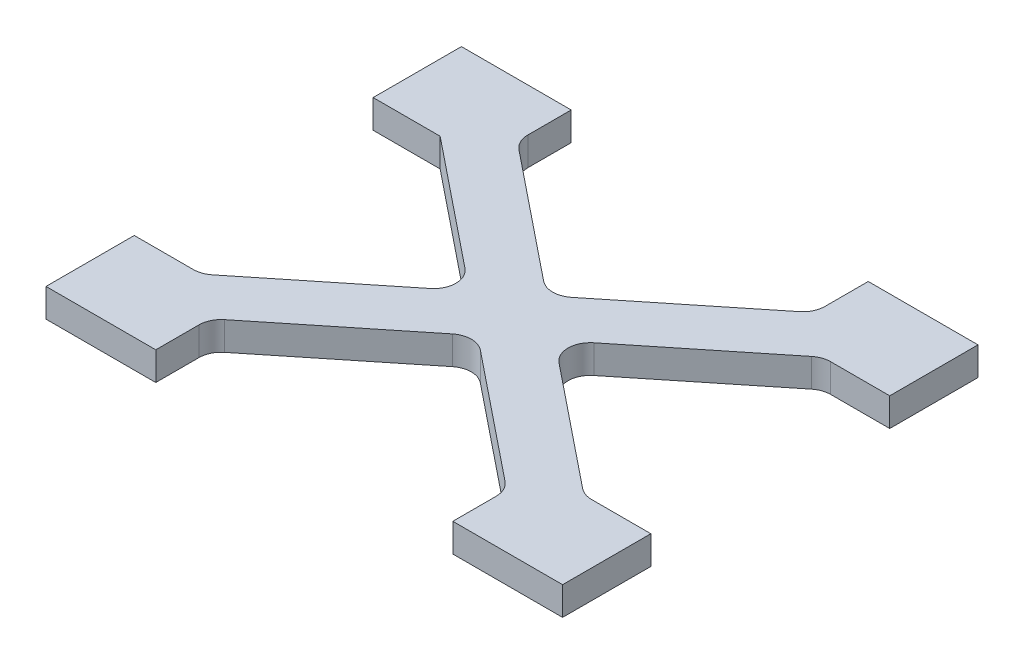
SolidWorks part; units mm, degrees
ref_plane "Front Plane" through (0, 0, 0) normal (0, 0, 1) x (1, 0, 0)
ref_plane "Top Plane" through (0, 0, 0) normal (0, 1, 0) x (1, 0, 0)
ref_plane "Right Plane" through (0, 0, 0) normal (1, 0, 0) x (0, 0, -1)
sketch "Sketch1" plane through (0, 0, 0) normal (0, 1, 0) x (1, 0, 0)
  line L1 (57.825, 46.5) -> (-57.825, 46.5) construction
  line L2 (57.825, 46.5) -> (57.825, -46.5) construction
  line L3 (57.825, -46.5) -> (-57.825, -46.5) construction
  line L4 (-57.825, 46.5) -> (-57.825, -46.5) construction
  line L5 (-57.825, 46.5) -> (57.825, -46.5) construction
  line L6 (-57.825, 26.7384) -> (-42.825, 26.7384)
  line L36 (-42.825, 26.7384) -> (-9.5745, 0)
  line L37 (-9.5745, 0) -> (-42.825, -26.7384)
  line L38 (-42.825, -26.7384) -> (-57.825, -26.7384)
  line L39 (-57.825, -26.7384) -> (-57.825, -46.5)
  line L40 (-57.825, -46.5) -> (-33.2505, -46.5)
  line L41 (-33.2505, -46.5) -> (-33.2505, -34.4377)
  line L42 (-33.2505, -34.4377) -> (0, -7.6993)
  line L43 (0, -7.6993) -> (33.2505, -34.4377)
  line L44 (33.2505, -34.4377) -> (33.2505, -46.5)
  line L45 (33.2505, -46.5) -> (57.825, -46.5)
  line L46 (57.825, -46.5) -> (57.825, -26.7384)
  line L47 (57.825, -26.7384) -> (42.825, -26.7384)
  line L48 (42.825, -26.7384) -> (9.5745, 0)
  line L49 (9.5745, 0) -> (42.825, 26.7384)
  line L50 (42.825, 26.7384) -> (57.825, 26.7384)
  line L51 (57.825, 26.7384) -> (57.825, 46.5)
  line L52 (57.825, 46.5) -> (33.2505, 46.5)
  line L53 (33.2505, 46.5) -> (33.2505, 34.4377)
  line L54 (33.2505, 34.4377) -> (0, 7.6993)
  line L55 (0, 7.6993) -> (-33.2505, 34.4377)
  line L56 (-33.2505, 34.4377) -> (-33.2505, 46.5)
  line L57 (-33.2505, 46.5) -> (-57.825, 46.5)
  line L58 (-57.825, 46.5) -> (-57.825, 26.7384)
  line L59 (-57.825, -46.5) -> (57.825, 46.5) construction
  line L65 (42.825, 26.7384) -> (33.2505, 34.4377) construction
  point P7 (0, 0)
  point P23 (50.7888, 42.9396)
  point P27 (50.3534, 42.5715)
  point P31 (0, 7.857)
  point P32 (-16.0474, 21.4243)
  dimension "D1" = 115.65
  dimension "D2" = 93
  dimension "D3" = 12
  dimension "D4" = 15
extrude "Boss-Extrude1" add sketch "Sketch1" along normal blind 6.35
fillet "Fillet1" radius 5 11 edges at (-33.2505, 3.175, -34.4377) (33.2505, 3.175, -34.4377) (42.825, 3.175, -26.7384) (42.825, 3.175, 26.7384) (33.2505, 3.175, 34.4377) (-33.2505, 3.175, 34.4377) (-42.825, 3.175, 26.7384) (-9.5745, 3.175, 0) (0, 3.175, -7.6993) (9.5745, 3.175, 0) (0, 3.175, 7.6993)
equation "\"L1L\"=500"
equation "\"L1Thick\"=6.35"
equation "\"Harm-Drive-Outer\"=74.5"
equation "\"L1-Spacing\"=115.65"
equation "\"L-Bracket-HoleToWall\"=12.5"
equation "\"L-Bracket-HoleToSide\"=11"
equation "\"Bracket-Hole-D\"=6.8"
equation "\"D1@Sketch1\"=\"L1-Spacing\""
